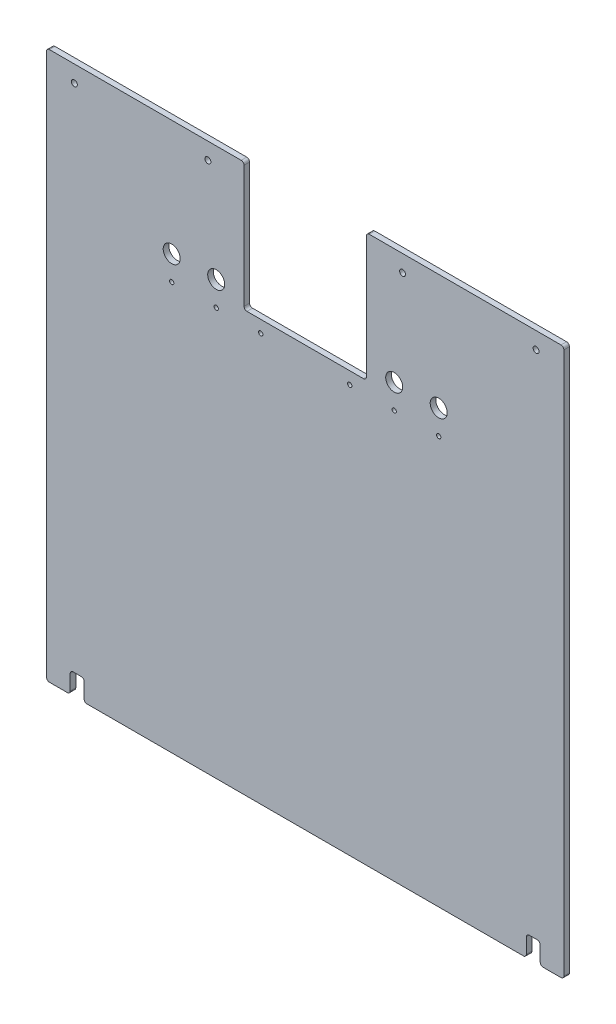
SolidWorks part; units mm, degrees
material "PC High Viscosity"
ref_plane "Front Plane" through (0, 0, 0) normal (0, 0, 1) x (1, 0, 0)
ref_plane "Top Plane" through (0, 0, 0) normal (0, 1, 0) x (1, 0, 0)
ref_plane "Right Plane" through (0, 0, 0) normal (1, 0, 0) x (0, 0, -1)
sketch "Sketch1" plane through (0, 0, 0) normal (0, 0, 1) x (1, 0, 0)
  line L1 (0, 0) -> (590.55, 0)
  line L2 (0, 0) -> (0, 479.425)
  line L3 (0, 479.425) -> (590.55, 479.425)
  line L4 (590.55, 0) -> (590.55, 479.425)
  dimension "D1" = 479.425
  dimension "D2" = 590.55
extrude "Boss-Extrude1" add sketch "Sketch1" along normal blind 6.35
sketch "Sketch2" plane through (0, 0, 6.35) normal (0, 0, 1) x (1, 0, 0)
  line L0 (0, 0) -> (590.55, 0) construction
  line L1 (31.75, 0) -> (38.1, 0) construction
  line L2 (31.75, 0) -> (31.75, 19.05) construction
  line L3 (31.75, 19.05) -> (38.1, 19.05) construction
  line L4 (38.1, 0) -> (38.1, 19.05) construction
  line L5 (295.275, 0) -> (295.275, 479.425) construction
  line L6 (590.55, 479.425) -> (0, 479.425) construction
  line L7 (552.45, 0) -> (552.45, 19.05) construction
  line L8 (558.8, 19.05) -> (552.45, 19.05) construction
  line L9 (558.8, 0) -> (558.8, 19.05) construction
  line L10 (558.8, 0) -> (552.45, 0) construction
  line L11 (26.9875, 0) -> (26.9875, 23.8125)
  line L12 (26.9875, 23.8125) -> (42.8625, 23.8125)
  line L13 (42.8625, 0) -> (42.8625, 23.8125)
  line L14 (42.8625, 0) -> (26.9875, 0)
  line L15 (563.5625, 23.8125) -> (547.6875, 23.8125)
  line L16 (563.5625, 0) -> (563.5625, 23.8125)
  line L17 (547.6875, 0) -> (547.6875, 23.8125)
  line L18 (547.6875, 0) -> (563.5625, 0)
  dimension "D1" = 6.35
  dimension "D2" = 527.05
  dimension "D3" = 19.05
  dimension "D4" = 4.7625
extrude "Cut-Extrude1" cut sketch "Sketch2" against normal through all
hole_wizard "#10 (0.1935) Diameter Hole1" positions "Sketch3" profile "Sketch4" hole size "#10" standard "ANSI Inch" end condition through all
sketch "Sketch3" plane through (0, 0, 6.35) normal (0, 0, 1) x (1, 0, 0)
  line L0 (295.275, 479.425) -> (295.275, 0) construction
  line L1 (590.55, 479.425) -> (0, 479.425) construction
  line L2 (42.8625, 0) -> (547.6875, 0) construction
  point P0 (142.875, 465.5078)
  point P2 (244.475, 465.5078)
  point P11 (346.075, 465.5078)
  point P12 (447.675, 465.5078)
  point P13 (193.675, 465.5078)
  point P16 (179.5097, 426.4054)
  point P17 (0, 0)
  point P18 (396.875, 465.5078)
  point P19 (0, 0)
  dimension "D1" = 101.6
  dimension "D2" = 101.6
  dimension "D3" = 13.9172
  dimension "D4" = 50.8
sketch "Sketch4" plane through (142.875, 465.5078, 6.35) normal (1, 0, 0) x (0, -1, 0)
  line L0 (0, 0) -> (0, 6.35)
  line L1 (0, 6.35) -> (2.4574, 6.35)
  line L2 (2.4574, 6.35) -> (2.4574, 0)
  line L5 (2.4574, 0) -> (0, 0)
  line L11 (0, -6.35) -> (0, 107.95) construction
  dimension "Thru Hole Dia." = 4.9149
  dimension "Thru Hole Depth" = 6.35
sketch "Sketch6" plane through (0, 0, 6.35) normal (0, 0, 1) x (1, 0, 0)
  line L0 (590.55, 479.425) -> (0, 479.425) construction
  line L1 (263.525, 479.425) -> (327.025, 479.425) construction
  line L2 (263.525, 479.425) -> (263.525, 809.625) construction
  line L3 (263.525, 809.625) -> (327.025, 809.625) construction
  line L4 (327.025, 479.425) -> (327.025, 809.625) construction
  line L5 (295.275, 479.425) -> (295.275, 809.625) construction
  line L6 (590.55, 625.475) -> (365.125, 625.475)
  line L7 (0, 479.425) -> (225.425, 479.425)
  line L8 (0, 479.425) -> (0, 625.475)
  line L9 (0, 625.475) -> (225.425, 625.475)
  line L10 (225.425, 479.425) -> (225.425, 625.475)
  line L11 (365.125, 479.425) -> (365.125, 625.475)
  line L12 (590.55, 479.425) -> (365.125, 479.425)
  line L13 (590.55, 479.425) -> (590.55, 625.475)
  line L14 (244.475, 465.5078) -> (244.475, 809.625) construction
  dimension "D1" = 63.5
  dimension "D2" = 330.2
  dimension "D3" = 146.05
  dimension "D4" = 19.05
extrude "Boss-Extrude3" add sketch "Sketch6" against normal up to surface (6.35 mm away) up to face at (145.3324, 465.5078, 0)
hole_wizard "49/64 (0.76563) Diameter Hole1" positions "Sketch7" profile "Sketch8" hole size "49/64" standard "ANSI Inch" end condition through all
sketch "Sketch7" plane through (0, 0, 6.35) normal (0, 0, 1) x (1, 0, 0)
  line L0 (142.875, 465.5078) -> (142.875, 493.3422) construction
  line L1 (365.125, 479.425) -> (225.425, 479.425) construction
  line L2 (365.125, 479.425) -> (225.425, 479.425) construction
  line L3 (295.275, 479.425) -> (295.275, 0) construction
  line L4 (42.8625, 0) -> (547.6875, 0) construction
  line L5 (193.675, 493.3422) -> (193.675, 465.5078) construction
  point P0 (142.875, 493.3422)
  point P13 (447.675, 493.3422)
  point P14 (193.675, 493.3422)
  point P17 (396.875, 493.3422)
sketch "Sketch8" plane through (142.875, 493.3422, 6.35) normal (1, 0, 0) x (0, -1, 0)
  line L0 (0, 0) -> (0, 6.35)
  line L1 (0, 6.35) -> (9.7235, 6.35)
  line L2 (9.7235, 6.35) -> (9.7235, 0)
  line L5 (9.7235, 0) -> (0, 0)
  line L11 (0, -6.35) -> (0, 107.95) construction
  dimension "Thru Hole Dia." = 19.447
  dimension "Thru Hole Depth" = 6.35
hole_wizard "1/4 Clearance Hole1" positions "Sketch9" profile "Sketch10" hole size "1/4" standard "ANSI Inch" end condition through all
sketch "Sketch9" plane through (0, 0, 6.35) normal (0, 0, 1) x (1, 0, 0)
  line L0 (295.275, 479.425) -> (295.275, 0) construction
  line L1 (365.125, 479.425) -> (225.425, 479.425) construction
  line L2 (42.8625, 0) -> (547.6875, 0) construction
  line L3 (0, 606.425) -> (225.425, 606.425) construction
  line L4 (0, 625.475) -> (0, 0) construction
  line L5 (225.425, 479.425) -> (225.425, 625.475) construction
  line L6 (225.425, 625.475) -> (0, 625.475) construction
  point P0 (31.75, 606.425)
  point P2 (184.15, 606.425)
  point P14 (406.4, 606.425)
  point P15 (558.8, 606.425)
  dimension "D1" = 19.05
  dimension "D2" = 31.75
  dimension "D3" = 152.4
sketch "Sketch10" plane through (31.75, 606.425, 6.35) normal (1, 0, 0) x (0, -1, 0)
  line L0 (0, 0) -> (0, 6.35)
  line L1 (0, 6.35) -> (3.3782, 6.35)
  line L2 (3.3782, 6.35) -> (3.3782, 0)
  line L5 (3.3782, 0) -> (0, 0)
  line L11 (0, -6.35) -> (0, 107.95) construction
  dimension "Thru Hole Dia." = 6.7564
  dimension "Thru Hole Depth" = 6.35
fillet "Fillet1" radius 3.302 16 edges at (26.9875, 23.8125, 3.175) (42.8625, 23.8125, 3.175) (42.8625, 0, 3.175) (547.6875, 0, 3.175) (547.6875, 23.8125, 3.175) (563.5625, 23.8125, 3.175) (563.5625, 0, 3.175) (590.55, 0, 3.175) (590.55, 625.475, 3.175) (365.125, 625.475, 3.175) (365.125, 479.425, 3.175) (225.425, 479.425, 3.175) (225.425, 625.475, 3.175) (0, 625.475, 3.175) (0, 0, 3.175) (26.9875, 0, 3.175)
equation "\"D3@Sketch6\"=1.75+4"
